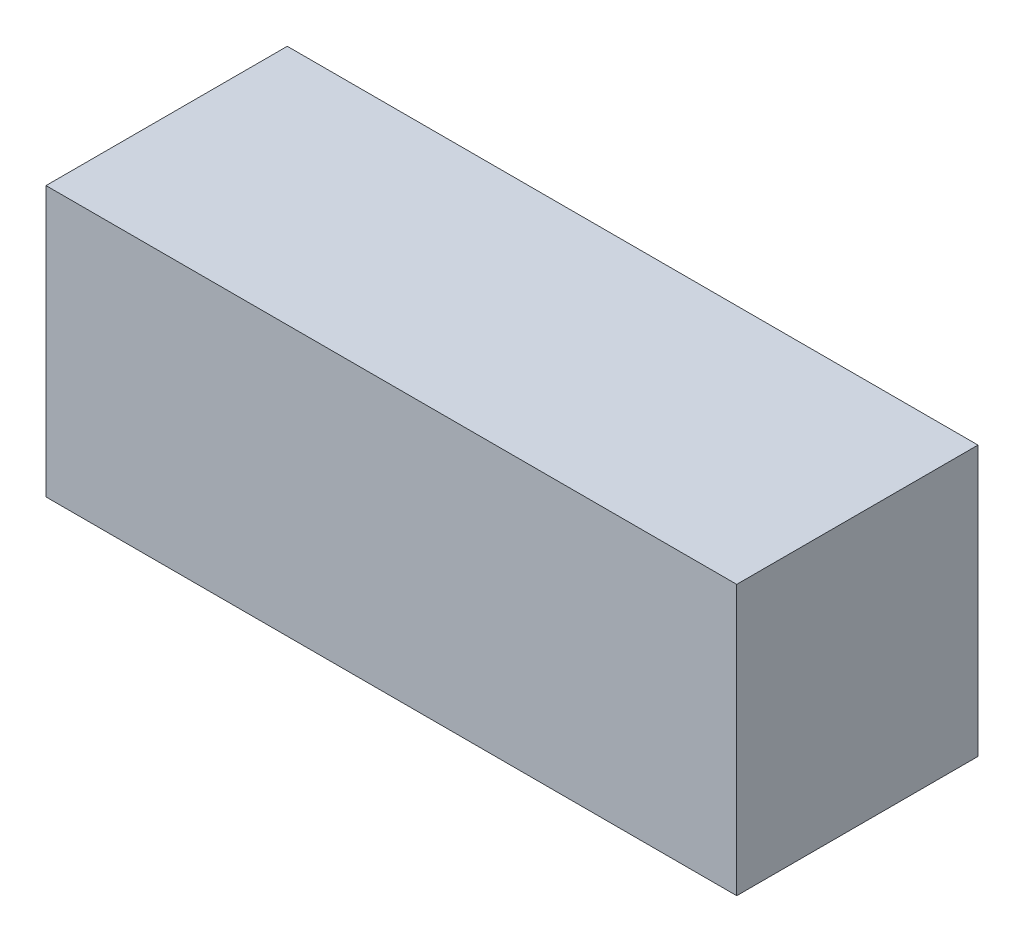
SolidWorks part; units mm, degrees
ref_plane "Front Plane" through (0, 0, 0) normal (0, 0, 1) x (1, 0, 0)
ref_plane "Top Plane" through (0, 0, 0) normal (0, 1, 0) x (1, 0, 0)
ref_plane "Right Plane" through (0, 0, 0) normal (1, 0, 0) x (0, 0, -1)
sketch "Sketch1" plane through (0, 0, 0) normal (0, 1, 0) x (1, 0, 0)
  line L1 (0, 0) -> (146, 0)
  line L2 (0, 0) -> (0, 51)
  line L3 (0, 51) -> (146, 51)
  line L4 (146, 0) -> (146, 51)
  dimension "D1" = 146
  dimension "D2" = 51
extrude "Boss-Extrude1" add sketch "Sketch1" along normal blind 57
